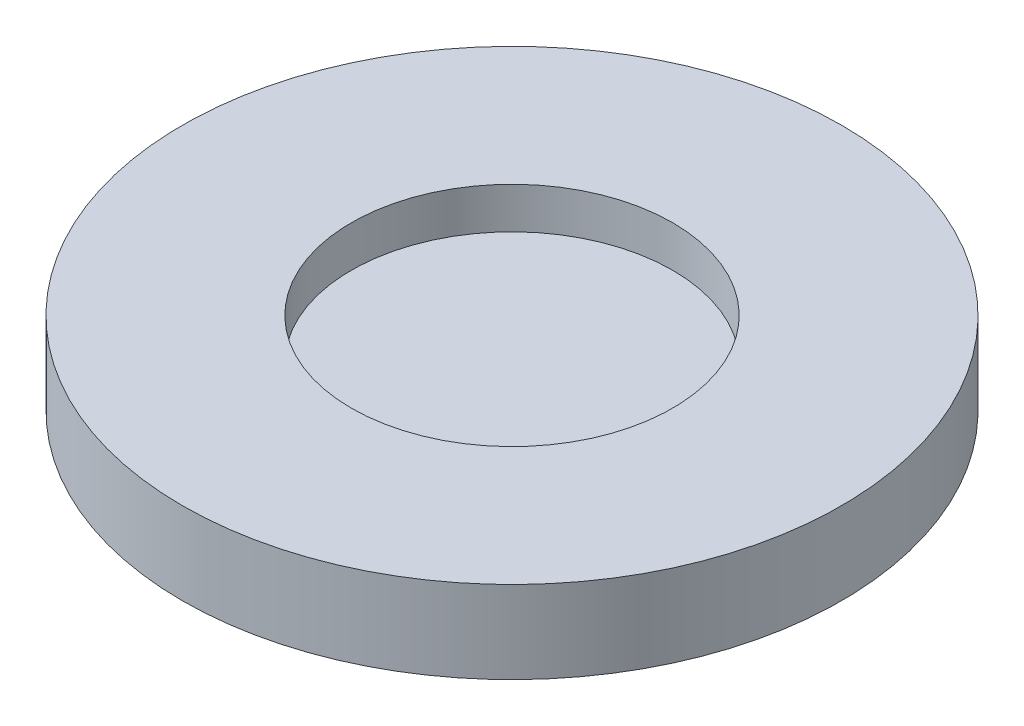
SolidWorks part; units mm, degrees
ref_plane "Front Plane" through (0, 0, 0) normal (0, 0, 1) x (1, 0, 0)
ref_plane "Top Plane" through (0, 0, 0) normal (0, 1, 0) x (1, 0, 0)
ref_plane "Right Plane" through (0, 0, 0) normal (1, 0, 0) x (0, 0, -1)
sketch "Sketch3" plane through (0, 0, 0) normal (0, 1, 0) x (1, 0, 0)
  circle A0 centre (0, 0) radius 40
extrude "Boss-Extrude3" add sketch "Sketch3" along normal blind 10
sketch "Sketch4" plane through (0, 10, 0) normal (0, 1, 0) x (1, 0, 0)
  circle A0 centre (0, 0) radius 19.5
extrude "Cut-Extrude1" cut sketch "Sketch4" against normal blind 5
